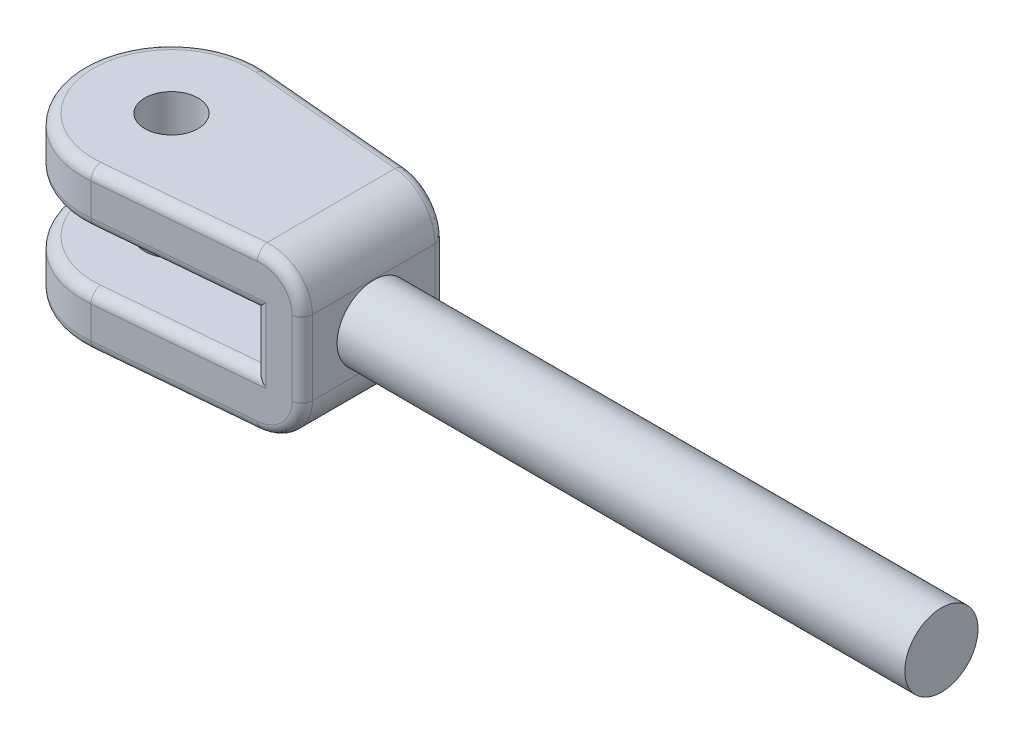
SolidWorks part; units mm, degrees
ref_plane "Front Plane" through (0, 0, 0) normal (0, 0, 1) x (1, 0, 0)
ref_plane "Top Plane" through (0, 0, 0) normal (0, 1, 0) x (1, 0, 0)
ref_plane "Right Plane" through (0, 0, 0) normal (1, 0, 0) x (0, 0, -1)
sketch "Sketch4" plane through (0, 0, 0) normal (1, 0, 0) x (0, 0, -1)
  circle A0 centre (0, 0) radius 2.6194
  dimension "D1" = 5.2387
extrude "Boss-Extrude2" add sketch "Sketch4" along normal blind 40.64
sketch "Sketch13" plane through (0, 0, 0) normal (0, 1, 0) x (1, 0, 0)
  line L6 (0, 5.08) -> (0, -5.08)
  line L7 (0, 0) -> (-16.4814, 0) construction
  line L10 (0, 5.08) -> (-13.9144, 6.3247)
  line L11 (0, -5.08) -> (-13.9144, -6.3247)
  arc A3 (-13.9144, 6.3247) -> (-13.9144, -6.3247) centre (-14.4802, 0) ccw
  point P2 (0, 0)
  dimension "D3" = 6.35
  dimension "D1" = 10.16
  dimension "D2" = 13.97
extrude "Boss-Extrude4" add sketch "Sketch13" along normal mid plane 11.43
sketch "Sketch16" plane through (0.4508, 0, 5.0397) normal (0.0891, 0, 0.996) x (0.996, 0, -0.0891)
  line L0 (-14.4226, -5.715) -> (-0.4526, -5.715) construction
  line L1 (-29.402, 1.905) -> (-3.6276, 1.905)
  line L2 (-29.402, 1.905) -> (-29.402, -1.905)
  line L3 (-29.402, -1.905) -> (-3.6276, -1.905)
  line L4 (-3.6276, 1.905) -> (-3.6276, -1.905)
  line L5 (-0.4526, 5.715) -> (-0.4526, -5.715) construction
  line L6 (-14.4226, 5.715) -> (-0.4526, 5.715) construction
  dimension "D1" = 3.81
  dimension "D2" = 3.175
  dimension "D3" = 3.81
extrude "Cut-Extrude2" cut sketch "Sketch16" against normal through all both and the other way through all
sketch "Sketch17" plane through (0, -5.715, 0) normal (0, -1, 0) x (1, 0, 0)
  circle A0 centre (-14.4802, 0) radius 1.905
  dimension "D1" = 3.81
extrude "Cut-Extrude3" cut sketch "Sketch17" against normal through all both
fillet "Fillet1" radius 3.048 2 edges at (0, -5.715, 0) (0, 5.715, 0)
fillet "Fillet2" radius 0.762 20 edges at (-8.4812, 5.715, -5.8387) (-0.8927, 4.8223, -5.1599) (-8.4812, -5.715, -5.8387) (-0.8927, -4.8223, -5.1599) (-8.4812, 5.715, 5.8387) (-0.8927, 4.8223, 5.1599) (0, 0, 5.08) (-0.8927, -4.8223, 5.1599) (-9.022, -1.905, -5.8871) (-9.022, 1.905, -5.8871) (-4.1296, 0, -5.4494) (0, 0, -5.08) (-8.5384, 1.905, 5.8438) (-8.5384, -1.905, 5.8438) (-3.1624, 0, 5.3629) (-8.4812, -5.715, 5.8387) (-20.8302, -5.715, 0) (-20.8302, -1.905, 0) (-20.8302, 1.905, 0) (-20.8302, 5.715, 0)
scale "Scale1" scale about centroid uniform scaling yes scale factor 6
